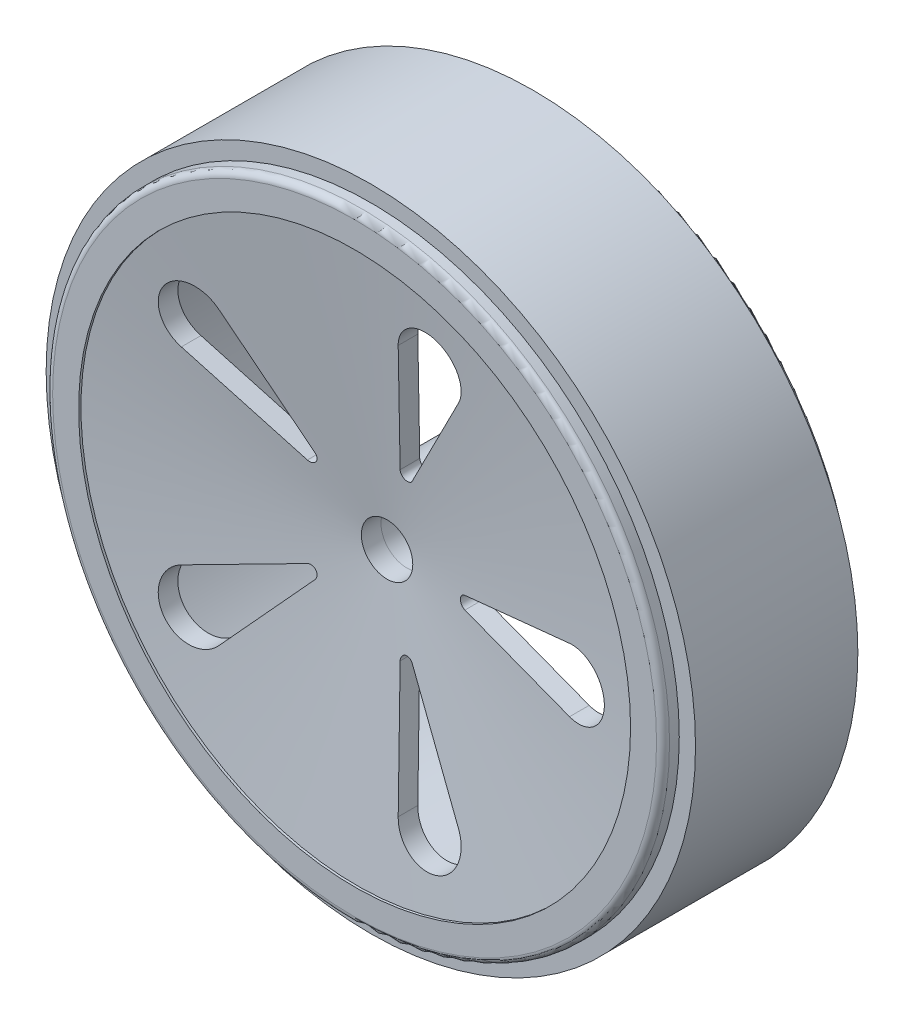
SolidWorks part; units mm, degrees
material "1060 Alloy"
ref_plane "Front Plane" through (0, 0, 0) normal (0, 0, 1) x (1, 0, 0)
ref_plane "Top Plane" through (0, 0, 0) normal (0, 1, 0) x (1, 0, 0)
ref_plane "Right Plane" through (0, 0, 0) normal (1, 0, 0) x (0, 0, -1)
sketch "Sketch1" plane through (0, 0, 0) normal (0, 0, 1) x (1, 0, 0)
  circle A0 centre (0, 0) radius 47.5
  circle A1 centre (0, 0) radius 42.5
  dimension "D1" = 95
  dimension "D2" = 85
extrude "Boss-Extrude1" add sketch "Sketch1" along normal mid plane 30
sketch "Sketch3" plane through (0, 0, 0) normal (0, 0, 1) x (1, 0, 0)
  circle A0 centre (0, 0) radius 8
  circle A1 centre (0, 0) radius 4
  dimension "D1" = 16
  dimension "D2" = 8
extrude "Boss-Extrude2" add sketch "Sketch3" along normal blind 10 and the other way blind 10 separate body
sketch "Sketch4" plane through (0, 0, 0) normal (0, 1, 0) x (1, 0, 0)
  line L0 (3.9602, -10) -> (45.4819, -15)
  line L3 (-42.5, -15) -> (42.5, -15) construction
  line L4 (3.9602, -6.9783) -> (45.4819, -11.9783)
  line L5 (-4, -10) -> (4, -10) construction
  line L6 (-47.5, -15) -> (47.5, -15) construction
  line L7 (45.4819, -11.9783) -> (45.4819, -15)
  line L8 (3.9602, -6.9783) -> (3.9602, -10)
  dimension "D1" = 3
revolve "Revolve1" add sketch "Sketch4" angle 360 about axis through (0, 0, -10) along (0, 0, 1)
sketch "Sketch5" plane through (0, 0, 15) normal (0, 0, 1) x (1, 0, 0)
  line L0 (0, 0) -> (42.5, 0) construction
  line L1 (13.0917, 0.9781) -> (31.4583, 4.8903)
  line L2 (31.4583, -4.8903) -> (13.0917, -0.9781)
  circle A0 centre (0, 0) radius 42.5 construction
  circle A1 centre (0, 0) radius 42.5 construction
  arc A2 (31.4583, 4.8903) -> (31.4583, -4.8903) centre (32.5, 0) cw
  circle A3 centre (0, 0) radius 32.5 construction
  arc A4 (13.0917, -0.9781) -> (13.0917, 0.9781) centre (13.3, 0) cw
  point P15 (8.5, 0)
  dimension "D1" = 5
  dimension "D2" = 65
  dimension "D4" = 1
  dimension "D3" = 24
extrude "Cut-Extrude1" cut sketch "Sketch5" against normal up to next
pattern_circular "CirPattern1" count 5 over 360 about axis through (0, 0, 0) along (0, 0, 1) of "Cut-Extrude1"
sketch "Sketch6" plane through (0, 0, 0) normal (0, 1, 0) x (1, 0, 0)
  circle A0 centre (0, 0) radius 1.5
  dimension "D1" = 3
extrude "Cut-Extrude2" cut sketch "Sketch6" against normal up to next
sketch "Sketch8" plane through (0, 0, 0) normal (0, 0, 1) x (1, 0, 0)
  circle A0 centre (0, 0) radius 50
  circle A1 centre (0, 0) radius 47.5 construction
  circle A2 centre (0, 0) radius 47.5
  dimension "D1" = 100
extrude "Boss-Extrude3" add sketch "Sketch8" along normal mid plane 25
fillet "Fillet1" radius 1 2 edges at (47.5, 0, 15) (47.5, 0, -15)
